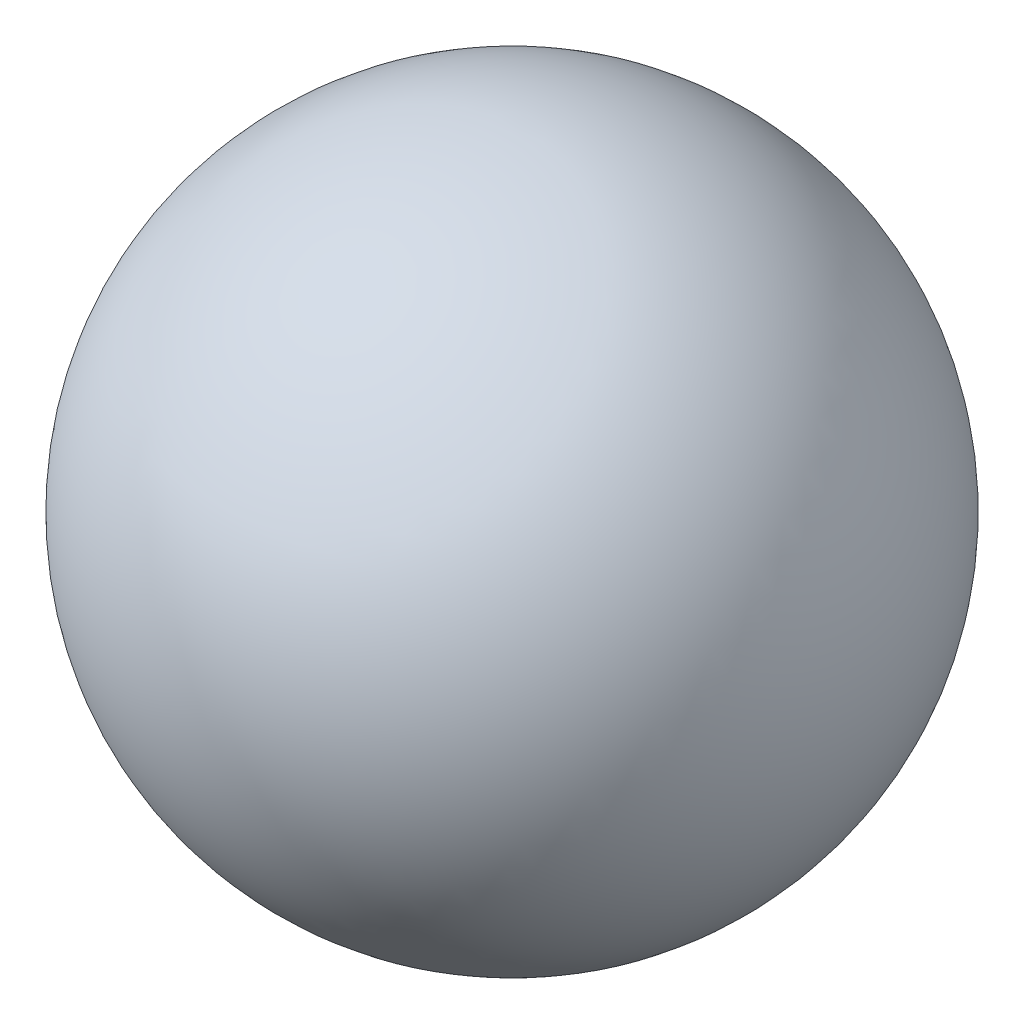
SolidWorks part; units mm, degrees
ref_plane "Front Plane" through (0, 0, 0) normal (0, 0, 1) x (1, 0, 0)
ref_plane "Top Plane" through (0, 0, 0) normal (0, 1, 0) x (1, 0, 0)
ref_plane "Right Plane" through (0, 0, 0) normal (1, 0, 0) x (0, 0, -1)
sketch "Sketch1" plane through (0, 0, 0) normal (0, 0, 1) x (1, 0, 0)
  line L0 (0, 50.8) -> (0, -50.8)
  line L1 (0, 50.8) -> (-40.7041, 50.8) construction
  arc A0 (0, 50.8) -> (0, -50.8) centre (0, 0) cw
  dimension "D1" = 50.8
revolve "Revolve1" add sketch "Sketch1" angle 360 about L0
